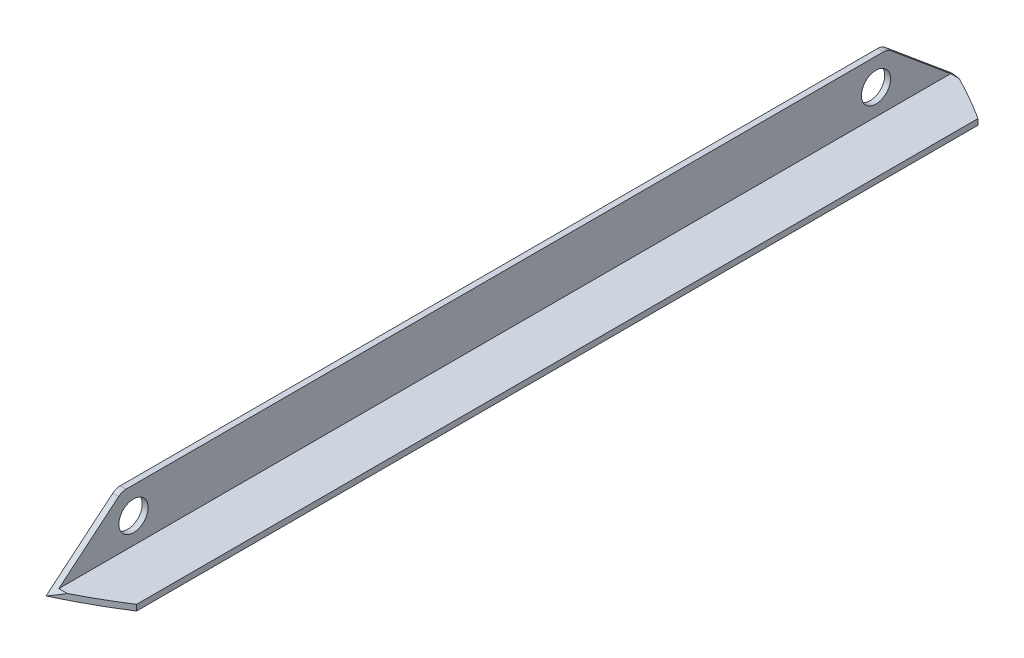
SolidWorks part; units mm, degrees
material "ASTM A36 Steel"
ref_plane "Front Plane" through (0, 0, 0) normal (0, 0, 1) x (1, 0, 0)
ref_plane "Top Plane" through (0, 0, 0) normal (0, 1, 0) x (1, 0, 0)
ref_plane "Right Plane" through (0, 0, 0) normal (1, 0, 0) x (0, 0, -1)
sketch "Sketch1" plane through (0, 0, 0) normal (0, 0, 1) x (1, 0, 0)
  line L0 (-14.0244, 39.2683) -> (-9.0244, 39.2683)
  line L1 (-9.0244, 39.2683) -> (-9.0244, -5.7317)
  line L2 (-9.0244, -5.7317) -> (35.9756, -5.7317)
  line L3 (35.9756, -5.7317) -> (35.9756, -10.7317)
  line L4 (35.9756, -10.7317) -> (-14.0244, -10.7317)
  line L5 (-14.0244, -10.7317) -> (-14.0244, 39.2683)
  dimension "D1" = 50
  dimension "D2" = 5
  dimension "D3" = 5
  dimension "D4" = 50
extrude "Boss-Extrude1" add sketch "Sketch1" along normal mid plane 1000 contours L4 L5 L0 L1 L2 L3
sketch "Sketch2" plane through (0, 39.2683, 0) normal (0, 1, 0) x (1, 0, 0)
  line L0 (-14.0244, -500) -> (-14.0244, 500) construction
  line L2 (-62.2243, 529.8977) -> (58.9688, 529.8977)
  line L3 (-62.2243, 529.8977) -> (-62.2243, 407.2387)
  line L5 (58.9688, 529.8977) -> (58.9688, 344.7397)
  line L6 (75.7296, -524.7406) -> (-50.6207, -524.7406)
  line L7 (75.7296, -524.7406) -> (75.7296, -341.6615)
  line L8 (75.7296, -341.6615) -> (63.0866, -341.6615)
  line L9 (-50.6207, -524.7406) -> (-50.6207, -403.2557)
  arc A0 (-50.6207, -403.2557) -> (63.0866, -341.6615) centre (-195.5244, 0) ccw
  arc A1 (58.9688, 344.7397) -> (-62.2243, 407.2387) centre (-195.5244, 0) ccw
  dimension "D1" = 857
  dimension "D2" = 181.5
extrude "Cut-Extrude1" cut sketch "Sketch2" against normal blind 70
sketch "Sketch3" plane through (-9.0244, 0, 0) normal (1, 0, 0) x (0, 0, -1)
  line L0 (388.1623, -10.7317) -> (328.1623, 39.2683)
  line L1 (-385.7849, 39.2683) -> (385.7849, 39.2683) construction
  line L2 (328.1623, 39.2683) -> (388.1623, 39.2683)
  line L3 (388.1623, 39.2683) -> (388.1623, -10.7317)
  dimension "D1" = 60
extrude "Cut-Extrude2" cut sketch "Sketch3" against normal mid plane 70
mirror "Mirror1" about plane through (0, 0, 0) normal (0, 0, 1) of "Cut-Extrude2"
fillet "Fillet1" radius 10 2 edges at (-11.5244, 39.2683, 328.1623) (-11.5244, 39.2683, -328.1623)
sketch "Sketch4" plane through (-9.0244, 0, 0) normal (1, 0, 0) x (0, 0, -1)
  line L0 (0, 27.5) -> (0, -27.5) construction
  line L1 (-324.5418, 39.2683) -> (324.5418, 39.2683) construction
  circle A0 centre (318.1623, 16.2683) radius 12.5
  circle A1 centre (-318.1623, 16.2683) radius 12.5
  dimension "D1" = 25
  dimension "D2" = 23
  dimension "D3" = 70
extrude "Cut-Extrude3" cut sketch "Sketch4" against normal blind 70
